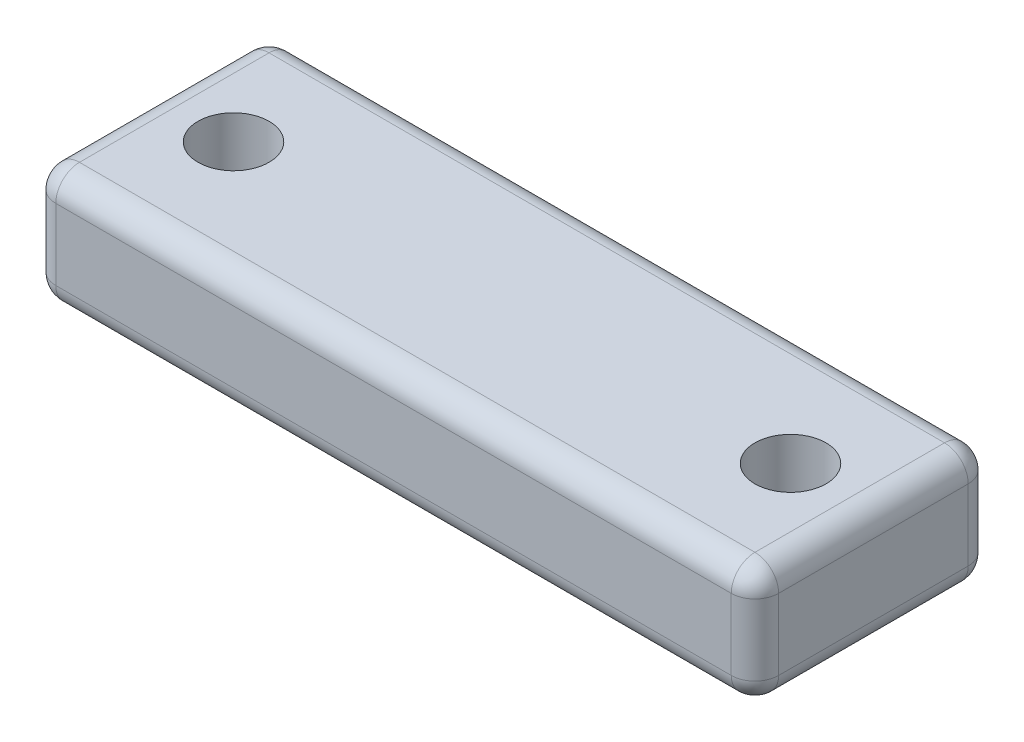
SolidWorks part; units mm, degrees
ref_plane "Front Plane" through (0, 0, 0) normal (0, 0, 1) x (1, 0, 0)
ref_plane "Top Plane" through (0, 0, 0) normal (0, 1, 0) x (1, 0, 0)
ref_plane "Right Plane" through (0, 0, 0) normal (1, 0, 0) x (0, 0, -1)
sketch "Sketch1" plane through (0, 0, 0) normal (0, 1, 0) x (1, 0, 0)
  line L1 (0, 0) -> (-30.5, 0)
  line L2 (0, 0) -> (0, 10)
  line L3 (0, 10) -> (-30.5, 10)
  line L4 (-30.5, 0) -> (-30.5, 10)
  dimension "D1" = 30.5
  dimension "D2" = 10
extrude "Boss-Extrude1" add sketch "Sketch1" along normal blind 5
sketch "Sketch2" plane through (0, 5, 0) normal (0, 1, 0) x (1, 0, 0)
  line L0 (0, 0) -> (0, 10) construction
  line L1 (0, 10) -> (-30.5, 10) construction
  line L4 (-30.5, 10) -> (-30.5, 0) construction
  circle A0 centre (-27, 5) radius 1.5
  circle A1 centre (-3.5, 5) radius 1.5
  dimension "D1" = 3
  dimension "D2" = 3
  dimension "D3" = 3.5
  dimension "D4" = 3.5
  dimension "D5" = 5
extrude "Cut-Extrude1" cut sketch "Sketch2" against normal through all both and the other way through all
fillet "Fillet1" radius 1 12 edges at (0, 5, -5) (0, 0, -5) (0, 2.5, -10) (-15.25, 5, -10) (-15.25, 0, -10) (-30.5, 2.5, -10) (-30.5, 5, -5) (-30.5, 0, -5) (-30.5, 2.5, 0) (-15.25, 5, 0) (0, 2.5, 0) (-15.25, 0, 0)
